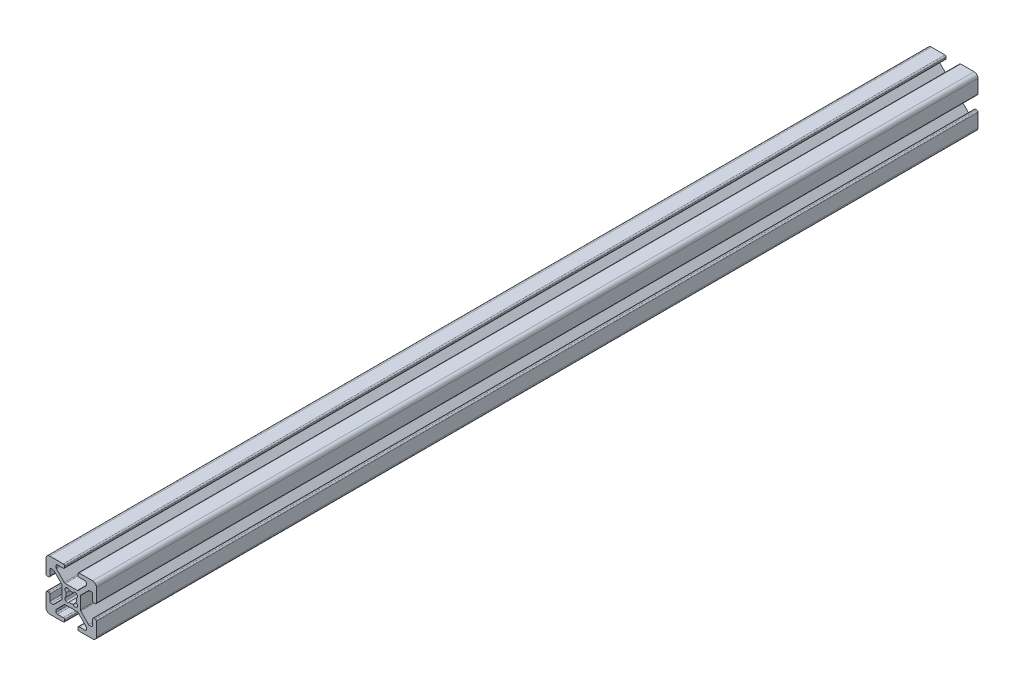
SolidWorks part; units mm, degrees
ref_plane "Front Plane" through (0, 0, 0) normal (0, 0, 1) x (1, 0, 0)
ref_plane "Top Plane" through (0, 0, 0) normal (0, 1, 0) x (1, 0, 0)
ref_plane "Right Plane" through (0, 0, 0) normal (1, 0, 0) x (0, 0, -1)
sketch "Sketch1" plane through (0, 0, 0) normal (0, 0, 1) x (1, 0, 0)
  line L0 (-5.0323, -0.3411) -> (-5.5163, -0.3411)
  line L1 (-6.0243, 0.1669) -> (-6.0243, 2.5159)
  line L2 (-4.5243, 0.1669) -> (-4.5243, 5.5289)
  line L3 (-10.8693, -5.355) -> (-10.8693, -0.5871)
  line L4 (-7.2582, 3.0239) -> (-6.5323, 3.0239)
  line L5 (-7.6174, 2.8752) -> (-10.7205, -0.2279)
  line L6 (-5.0323, -5.6011) -> (-5.5163, -5.6011)
  line L7 (-4.5243, -6.1091) -> (-4.5243, -11.4711)
  line L8 (-6.0243, -6.1091) -> (-6.0243, -8.4581)
  line L9 (-7.2582, -8.9661) -> (-6.5323, -8.9661)
  line L10 (-7.6174, -8.8173) -> (-10.7205, -5.7142)
  line L11 (-12.3994, -5.2756) -> (-12.2198, -5.096)
  line L12 (-17.1543, 6.5209) -> (-17.1543, 6.0369)
  line L13 (-17.6623, 7.0289) -> (-23.0243, 7.0289)
  line L14 (-17.6623, 5.5289) -> (-20.0113, 5.5289)
  line L15 (-12.1404, 0.6839) -> (-16.9082, 0.6839)
  line L16 (-20.5193, 4.295) -> (-20.5193, 5.0209)
  line L17 (-20.3705, 3.9358) -> (-17.2674, 0.8327)
  line L18 (-11.8943, 6.5209) -> (-11.8943, 6.0369)
  line L19 (-11.3863, 7.0289) -> (-6.0243, 7.0289)
  line L20 (-11.3863, 5.5289) -> (-9.0373, 5.5289)
  line L21 (-8.5293, 4.295) -> (-8.5293, 5.0209)
  line L22 (-8.6781, 3.9358) -> (-11.7812, 0.8327)
  line L23 (-12.2198, -0.8462) -> (-12.3994, -0.6666)
  line L24 (-24.0163, -5.6011) -> (-23.5323, -5.6011)
  line L25 (-24.5243, -6.1091) -> (-24.5243, -11.4711)
  line L26 (-23.0243, -6.1091) -> (-23.0243, -8.4581)
  line L27 (-18.1793, -0.5871) -> (-18.1793, -5.355)
  line L28 (-21.7904, -8.9661) -> (-22.5163, -8.9661)
  line L29 (-21.4312, -8.8173) -> (-18.3281, -5.7142)
  line L30 (-24.0163, -0.3411) -> (-23.5323, -0.3411)
  line L31 (-24.5243, 0.1669) -> (-24.5243, 5.5289)
  line L32 (-23.0243, 0.1669) -> (-23.0243, 2.5159)
  line L33 (-21.7904, 3.0239) -> (-22.5163, 3.0239)
  line L34 (-21.4312, 2.8752) -> (-18.3281, -0.2279)
  line L35 (-16.6492, -0.6666) -> (-16.8288, -0.8462)
  line L36 (-11.8943, -12.4631) -> (-11.8943, -11.9791)
  line L37 (-11.3863, -12.9711) -> (-6.0243, -12.9711)
  line L38 (-11.3863, -11.4711) -> (-9.0373, -11.4711)
  line L39 (-16.9082, -6.6261) -> (-12.1404, -6.6261)
  line L40 (-8.5293, -10.2371) -> (-8.5293, -10.9631)
  line L41 (-8.6781, -9.8779) -> (-11.7812, -6.7748)
  line L42 (-17.1543, -12.4631) -> (-17.1543, -11.9791)
  line L43 (-17.6623, -12.9711) -> (-23.0243, -12.9711)
  line L44 (-17.6623, -11.4711) -> (-20.0113, -11.4711)
  line L45 (-20.5193, -10.2371) -> (-20.5193, -10.9631)
  line L46 (-20.3705, -9.8779) -> (-17.2674, -6.7748)
  line L47 (-16.8288, -5.096) -> (-16.6492, -5.2756)
  arc A0 (-15.3283, -4.9062) -> (-13.7203, -4.9062) centre (-14.5243, -2.9711) ccw
  arc A1 (-6.0243, 2.5159) -> (-6.5323, 3.0239) centre (-6.5323, 2.5159) ccw
  arc A2 (-7.2582, 3.0239) -> (-7.6174, 2.8752) centre (-7.2582, 2.5159) ccw
  arc A3 (-10.7205, -0.2279) -> (-10.8693, -0.5871) centre (-10.3613, -0.5871) ccw
  arc A4 (-10.8693, -5.355) -> (-10.7205, -5.7142) centre (-10.3613, -5.355) ccw
  arc A5 (-7.6174, -8.8173) -> (-7.2582, -8.9661) centre (-7.2582, -8.4581) ccw
  arc A6 (-6.5323, -8.9661) -> (-6.0243, -8.4581) centre (-6.5323, -8.4581) ccw
  arc A7 (-5.5163, -5.6011) -> (-6.0243, -6.1091) centre (-5.5163, -6.1091) ccw
  arc A8 (-4.5243, -6.1091) -> (-5.0323, -5.6011) centre (-5.0323, -6.1091) ccw
  arc A9 (-5.0323, -0.3411) -> (-4.5243, 0.1669) centre (-5.0323, 0.1669) ccw
  arc A10 (-6.0243, 0.1669) -> (-5.5163, -0.3411) centre (-5.5163, 0.1669) ccw
  arc A11 (-13.7203, -4.9062) -> (-12.3994, -5.2756) centre (-12.9559, -4.7191) ccw
  arc A12 (-12.2198, -5.096) -> (-12.5892, -3.775) centre (-12.7763, -4.5395) ccw
  arc A13 (-17.1543, 6.5209) -> (-17.6623, 7.0289) centre (-17.6623, 6.5209) ccw
  arc A14 (-17.6623, 5.5289) -> (-17.1543, 6.0369) centre (-17.6623, 6.0369) ccw
  arc A15 (-12.5892, -3.775) -> (-12.5892, -2.1671) centre (-14.5243, -2.9711) ccw
  arc A16 (-17.2674, 0.8327) -> (-16.9082, 0.6839) centre (-16.9082, 1.1919) ccw
  arc A17 (-20.0113, 5.5289) -> (-20.5193, 5.0209) centre (-20.0113, 5.0209) ccw
  arc A18 (-20.5193, 4.295) -> (-20.3705, 3.9358) centre (-20.0113, 4.295) ccw
  arc A19 (-11.8943, 6.0369) -> (-11.3863, 5.5289) centre (-11.3863, 6.0369) ccw
  arc A20 (-11.3863, 7.0289) -> (-11.8943, 6.5209) centre (-11.3863, 6.5209) ccw
  arc A21 (-8.5293, 5.0209) -> (-9.0373, 5.5289) centre (-9.0373, 5.0209) ccw
  arc A22 (-8.6781, 3.9358) -> (-8.5293, 4.295) centre (-9.0373, 4.295) ccw
  arc A23 (-12.1404, 0.6839) -> (-11.7812, 0.8327) centre (-12.1404, 1.1919) ccw
  arc A24 (-12.5892, -2.1671) -> (-12.2198, -0.8462) centre (-12.7763, -1.4027) ccw
  arc A25 (-12.3994, -0.6666) -> (-13.7203, -1.0359) centre (-12.9559, -1.223) ccw
  arc A26 (-24.0163, -5.6011) -> (-24.5243, -6.1091) centre (-24.0163, -6.1091) ccw
  arc A27 (-23.0243, -6.1091) -> (-23.5323, -5.6011) centre (-23.5323, -6.1091) ccw
  arc A28 (-13.7203, -1.0359) -> (-15.3283, -1.0359) centre (-14.5243, -2.9711) ccw
  arc A29 (-18.3281, -5.7142) -> (-18.1793, -5.355) centre (-18.6873, -5.355) ccw
  arc A30 (-23.0243, -8.4581) -> (-22.5163, -8.9661) centre (-22.5163, -8.4581) ccw
  arc A31 (-21.7904, -8.9661) -> (-21.4312, -8.8173) centre (-21.7904, -8.4581) ccw
  arc A32 (-23.5323, -0.3411) -> (-23.0243, 0.1669) centre (-23.5323, 0.1669) ccw
  arc A33 (-24.5243, 0.1669) -> (-24.0163, -0.3411) centre (-24.0163, 0.1669) ccw
  arc A34 (-22.5163, 3.0239) -> (-23.0243, 2.5159) centre (-22.5163, 2.5159) ccw
  arc A35 (-21.4312, 2.8752) -> (-21.7904, 3.0239) centre (-21.7904, 2.5159) ccw
  arc A36 (-18.1793, -0.5871) -> (-18.3281, -0.2279) centre (-18.6873, -0.5871) ccw
  arc A37 (-15.3283, -1.0359) -> (-16.6492, -0.6666) centre (-16.0927, -1.223) ccw
  arc A38 (-16.8288, -0.8462) -> (-16.4594, -2.1671) centre (-16.2723, -1.4027) ccw
  arc A39 (-11.8943, -12.4631) -> (-11.3863, -12.9711) centre (-11.3863, -12.4631) ccw
  arc A40 (-11.3863, -11.4711) -> (-11.8943, -11.9791) centre (-11.3863, -11.9791) ccw
  arc A41 (-16.4594, -2.1671) -> (-16.4594, -3.775) centre (-14.5243, -2.9711) ccw
  arc A42 (-11.7812, -6.7748) -> (-12.1404, -6.6261) centre (-12.1404, -7.1341) ccw
  arc A43 (-9.0373, -11.4711) -> (-8.5293, -10.9631) centre (-9.0373, -10.9631) ccw
  arc A44 (-8.5293, -10.2371) -> (-8.6781, -9.8779) centre (-9.0373, -10.2371) ccw
  arc A45 (-17.1543, -11.9791) -> (-17.6623, -11.4711) centre (-17.6623, -11.9791) ccw
  arc A46 (-17.6623, -12.9711) -> (-17.1543, -12.4631) centre (-17.6623, -12.4631) ccw
  arc A47 (-20.5193, -10.9631) -> (-20.0113, -11.4711) centre (-20.0113, -10.9631) ccw
  arc A48 (-20.3705, -9.8779) -> (-20.5193, -10.2371) centre (-20.0113, -10.2371) ccw
  arc A49 (-16.9082, -6.6261) -> (-17.2674, -6.7748) centre (-16.9082, -7.1341) ccw
  arc A50 (-16.4594, -3.775) -> (-16.8288, -5.096) centre (-16.2723, -4.5395) ccw
  arc A51 (-16.6492, -5.2756) -> (-15.3283, -4.9062) centre (-16.0927, -4.7191) ccw
  arc A52 (-4.5243, 5.5289) -> (-6.0243, 7.0289) centre (-6.0243, 5.5289) ccw
  arc A53 (-6.0243, -12.9711) -> (-4.5243, -11.4711) centre (-6.0243, -11.4711) ccw
  arc A54 (-24.5243, -11.4711) -> (-23.0243, -12.9711) centre (-23.0243, -11.4711) ccw
  arc A55 (-23.0243, 7.0289) -> (-24.5243, 5.5289) centre (-23.0243, 5.5289) ccw
extrude "Extrude1" add sketch "Sketch1" along normal blind 350
